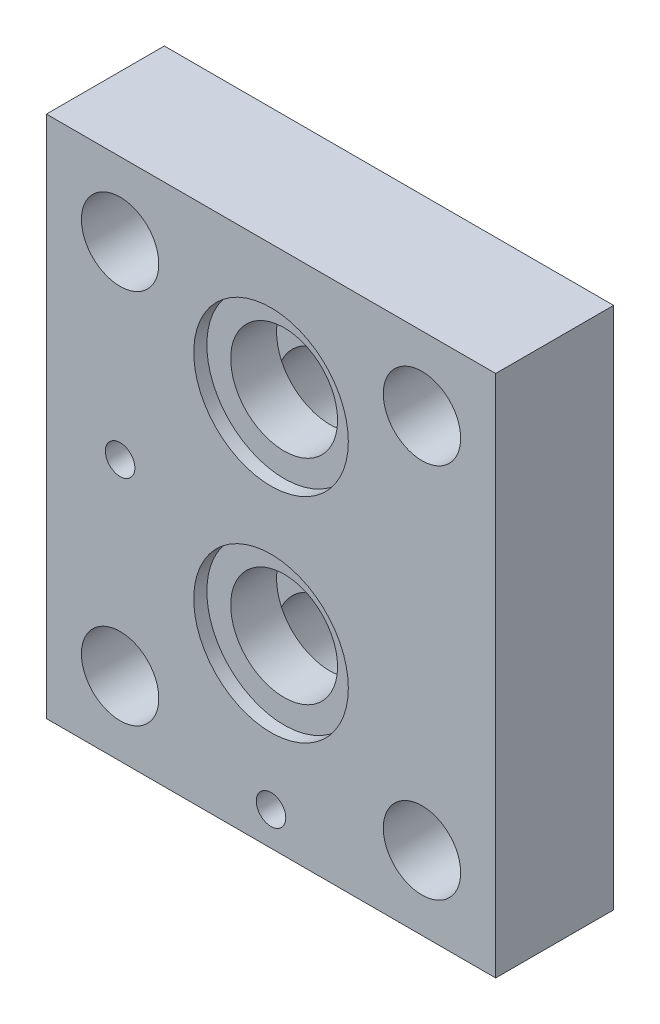
SolidWorks part; units mm, degrees
ref_plane "Front Plane" through (0, 0, 0) normal (1, 0, 0) x (0, 1, 0)
ref_plane "Top Plane" through (0, 0, 0) normal (0, 0, 1) x (0, 1, 0)
ref_plane "Right Plane" through (0, 0, 0) normal (0, 1, 0) x (-1, 0, 0)
sketch "Sketch1" plane through (0, 0, 0) normal (0, 0, 1) x (0, 1, 0)
  line L1 (-56.388, -48.387) -> (56.388, -48.387)
  line L2 (-56.388, -48.387) -> (-56.388, 48.387)
  line L3 (-56.388, 48.387) -> (56.388, 48.387)
  line L4 (56.388, -48.387) -> (56.388, 48.387)
  line L5 (-56.388, -48.387) -> (56.388, 48.387) construction
  line L6 (-56.388, 48.387) -> (56.388, -48.387) construction
  point P0 (0, 0)
extrude "Boss-Extrude1" add sketch "Sketch1" along normal mid plane 25.4
hole_wizard "5/8 Clearance Hole1" positions "Sketch3" profile "Sketch2" hole size "5/8" standard "ANSI Inch"
sketch "Sketch3" plane through (0, 0, -12.7) normal (0, 0, -1) x (-1, 0, 0)
  point P0 (-32.512, -40.513)
sketch "Sketch2" plane through (32.512, -40.513, -12.7) normal (1, 0, 0) x (0, 1, 0)
  line L0 (0, 0) -> (0, 30.4078)
  line L1 (0, 30.4078) -> (8.3344, 25.4)
  line L2 (8.3344, 25.4) -> (8.3344, 0)
  line L5 (8.3344, 0) -> (0, 0)
  line L10 (0, 30.4078) -> (-8.3344, 25.4) construction
  line L11 (0, -6.35) -> (0, 107.95) construction
  dimension "Hole Dia." = 16.6687
  dimension "Hole Depth" = 25.4
  dimension "Drill Angle" = 118
hole_wizard "5/8 Clearance Hole2" positions "Sketch5" profile "Sketch4" hole size "5/8" standard "ANSI Inch"
sketch "Sketch5" plane through (0, 0, -12.7) normal (0, 0, -1) x (-1, 0, 0)
  point P0 (-32.512, 40.513)
  point P1 (32.512, -40.513)
  point P3 (32.512, 40.513)
sketch "Sketch4" plane through (32.512, 40.513, -12.7) normal (1, 0, 0) x (0, 1, 0)
  line L0 (0, 0) -> (0, 30.4078)
  line L1 (0, 30.4078) -> (8.3344, 25.4)
  line L2 (8.3344, 25.4) -> (8.3344, 0)
  line L5 (8.3344, 0) -> (0, 0)
  line L10 (0, 30.4078) -> (-8.3344, 25.4) construction
  line L11 (0, -6.35) -> (0, 107.95) construction
  dimension "Hole Dia." = 16.6687
  dimension "Hole Depth" = 25.4
  dimension "Drill Angle" = 118
sketch "Sketch6" plane through (0, 0, 0) normal (0, 0, 1) x (0, 1, 0)
  circle A0 centre (-27.813, 0) radius 11.5094
extrude "Cut-Extrude2" cut sketch "Sketch6" along normal blind 12.7 from offset 12.7
sketch "Sketch7" plane through (0, 0, 0) normal (0, 0, 1) x (0, 1, 0)
  circle A0 centre (18.161, 0) radius 11.5094
extrude "Cut-Extrude4" cut sketch "Sketch7" along normal blind 12.7 from offset 12.7
sketch "Sketch8" plane through (0, 0, 0) normal (0, 0, 1) x (0, 1, 0)
  circle A0 centre (-18.161, 0) radius 11.5094
extrude "Cut-Extrude6" cut sketch "Sketch8" against normal blind 12.7 from offset 12.7
sketch "Sketch9" plane through (0, 0, 0) normal (0, 0, 1) x (0, 1, 0)
  circle A0 centre (27.813, 0) radius 11.5094
extrude "Cut-Extrude8" cut sketch "Sketch9" against normal blind 12.7 from offset 12.7
sketch "Sketch10" plane through (0, 0, 0) normal (0, 0, 1) x (0, 1, 0)
  circle A0 centre (-18.161, 0) radius 16.6497
extrude "Cut-Extrude10" cut sketch "Sketch10" against normal blind 2.8194 from offset 12.7
sketch "Sketch11" plane through (0, 0, 0) normal (0, 0, 1) x (0, 1, 0)
  circle A0 centre (27.813, 0) radius 16.6497
extrude "Cut-Extrude12" cut sketch "Sketch11" against normal blind 2.8194 from offset 12.7
sketch "Sketch12" plane through (0, 0, 0) normal (0, 0, 1) x (0, 1, 0)
  circle A0 centre (49.149, 0) radius 3.5719
  circle A1 centre (0.127, -32.512) radius 3.5719
extrude "Cut-Extrude14" cut sketch "Sketch12" along normal blind 7.874 from offset 12.7
sketch "Sketch13" plane through (0, 0, 0) normal (0, 0, 1) x (0, 1, 0)
  circle A0 centre (-49.149, 0) radius 3.175
  circle A1 centre (-0.127, 32.512) radius 3.175
extrude "Cut-Extrude16" cut sketch "Sketch13" against normal blind 7.874 from offset 12.7
